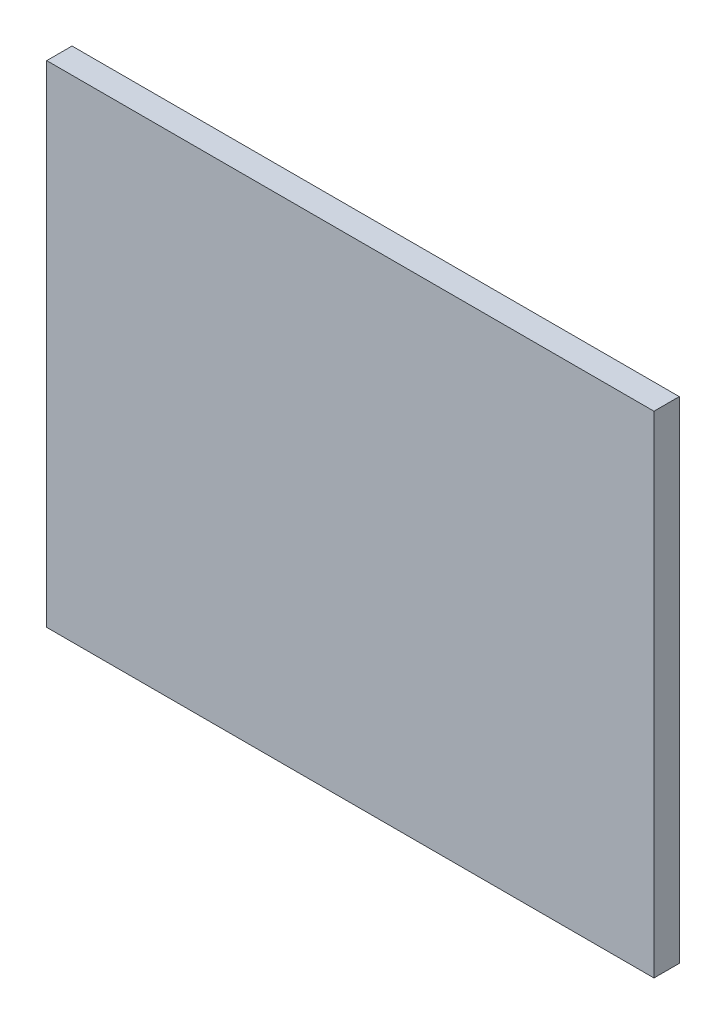
SolidWorks part; units mm, degrees
material "ABS"
ref_plane "Front Plane" through (0, 0, 0) normal (0, 0, 1) x (1, 0, 0)
ref_plane "Top Plane" through (0, 0, 0) normal (0, 1, 0) x (1, 0, 0)
ref_plane "Right Plane" through (0, 0, 0) normal (1, 0, 0) x (0, 0, -1)
sketch "Sketch1" plane through (0, 0, 0) normal (0, 0, 1) x (1, 0, 0)
  line L1 (-69.0775, 40.5904) -> (50.9225, 40.5904)
  line L2 (-69.0775, 40.5904) -> (-69.0775, -56.4096)
  line L3 (-69.0775, -56.4096) -> (50.9225, -56.4096)
  line L4 (50.9225, 40.5904) -> (50.9225, -56.4096)
  dimension "D1" = 120
  dimension "D2" = 97
extrude "Boss-Extrude1" add sketch "Sketch1" along normal blind 5
